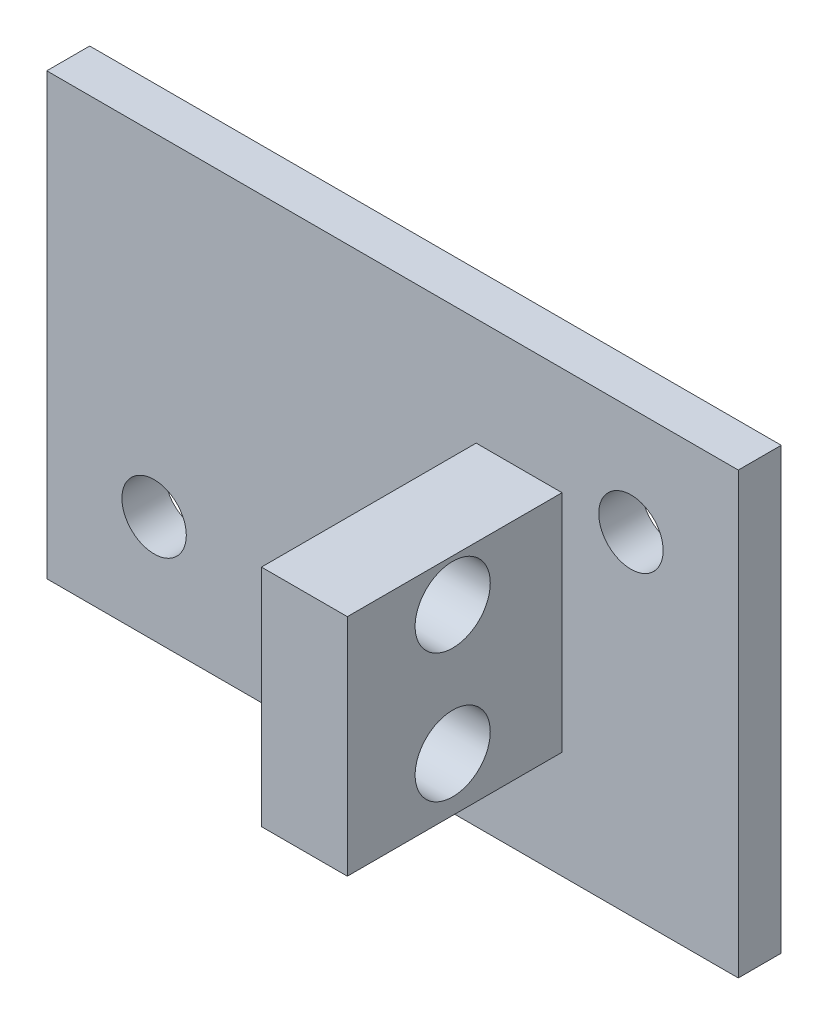
SolidWorks part; units mm, degrees
ref_plane "Plan de face" through (0, 0, 0) normal (0, 0, 1) x (1, 0, 0)
ref_plane "Plan de dessus" through (0, 0, 0) normal (0, 1, 0) x (1, 0, 0)
ref_plane "Plan de droite" through (0, 0, 0) normal (1, 0, 0) x (0, 0, -1)
sketch "Esquisse1" plane through (0, 0, 0) normal (0, 0, 1) x (1, 0, 0)
  line L1 (0, 0) -> (32.21, 0)
  line L2 (0, 0) -> (0, 20.49)
  line L3 (0, 20.49) -> (32.21, 20.49)
  line L4 (32.21, 0) -> (32.21, 20.49)
  circle A0 centre (5, 5) radius 1.5
  circle A1 centre (27.21, 15.49) radius 1.5
  point P11 (16.1235, 12.5024)
  dimension "D1" = 3
  dimension "D2" = 3
  dimension "D3" = 22.21
  dimension "D4" = 10.49
  dimension "D5" = 5
  dimension "D6" = 5
  dimension "D7" = 5
  dimension "D8" = 5
extrude "Boss.-Extru.1" add sketch "Esquisse1" along normal blind 2 contours A1 L3 L2 L1 L4 A0
sketch "Esquisse2" plane through (0, 0, 2) normal (0, 0, 1) x (1, 0, 0)
  line L0 (0, 0) -> (32.21, 0) construction
  line L1 (24, 15.4712) -> (20, 15.4712)
  line L2 (24, 15.4712) -> (24, 5)
  line L3 (24, 5) -> (20, 5)
  line L4 (20, 15.4712) -> (20, 5)
  line L5 (0, 0) -> (0, 20.49) construction
  dimension "D1" = 4
  dimension "D2" = 10.4712
  dimension "D3" = 5
  dimension "D4" = 20
extrude "Boss.-Extru.2" add sketch "Esquisse2" along normal blind 10
sketch "Esquisse3" plane through (24, 0, 0) normal (1, 0, 0) x (0, 0, -1)
  line L0 (-12, 5) -> (-2, 5) construction
  circle A0 centre (-7.0925, 13.5) radius 1.75
  circle A1 centre (-7.0925, 7.5) radius 1.75
  point P8 (-7.4061, 8.0311)
  dimension "D1" = 3.5
  dimension "D2" = 3.5
  dimension "D3" = 2.5
  dimension "D4" = 6
  dimension "D5" = 0
extrude "Enlèv. mat.-Extru.1" cut sketch "Esquisse3" against normal blind 10
